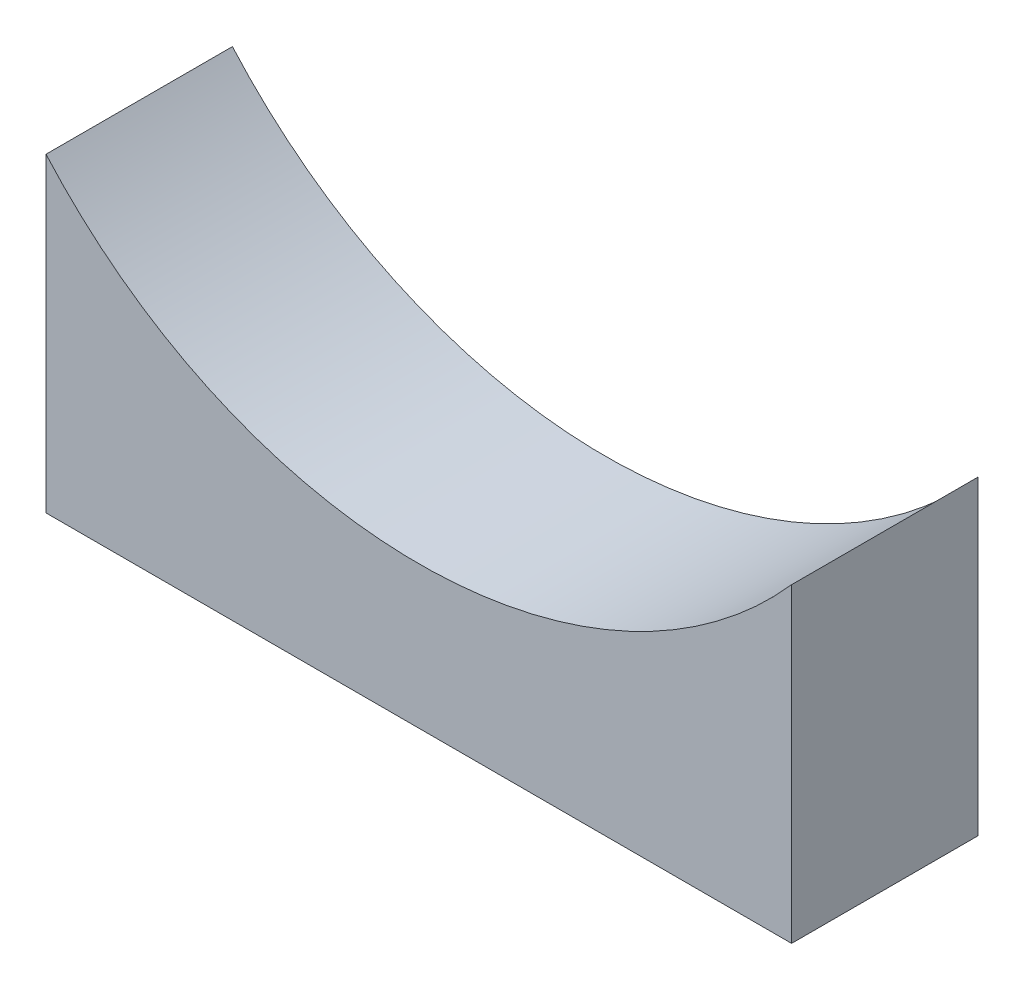
SolidWorks part; units mm, degrees
ref_plane "Front Plane" through (0, 0, 0) normal (0, 0, 1) x (1, 0, 0)
ref_plane "Top Plane" through (0, 0, 0) normal (0, 1, 0) x (1, 0, 0)
ref_plane "Right Plane" through (0, 0, 0) normal (1, 0, 0) x (0, 0, -1)
sketch "Sketch1" plane through (0, 0, 0) normal (0, 0, 1) x (1, 0, 0)
  line L0 (-38.1, 50.8) -> (-38.1, 0)
  line L1 (-38.1, 0) -> (38.1, 0)
  line L2 (38.1, 0) -> (38.1, 50.8)
  arc A0 (-38.1, 50.8) -> (38.1, 50.8) centre (0, 84.401) ccw
  point P5 (0, 0)
  dimension "D1" = 50.8
  dimension "D2" = 50.8
  dimension "D3" = 76.2
extrude "Boss-Extrude1" add sketch "Sketch1" along normal blind 19.05
sketch "Sketch2" plane through (0, 0, 0) normal (0, -1, 0) x (1, 0, 0)
  line L4 (-38.1, 0) -> (38.1, 0)
  line L5 (38.1, 0) -> (38.1, 19.05)
  line L6 (38.1, 19.05) -> (-38.1, 19.05)
  line L7 (-38.1, 19.05) -> (-38.1, 0)
  line L8 (-38.1, 0) -> (38.1, 0)
  line L9 (38.1, 0) -> (38.1, 19.05)
  line L10 (38.1, 19.05) -> (-38.1, 19.05)
  line L11 (-38.1, 19.05) -> (-38.1, 0)
  dimension "D1" = 0
extrude "Cut-Extrude1" cut sketch "Sketch2" against normal blind 19.05
